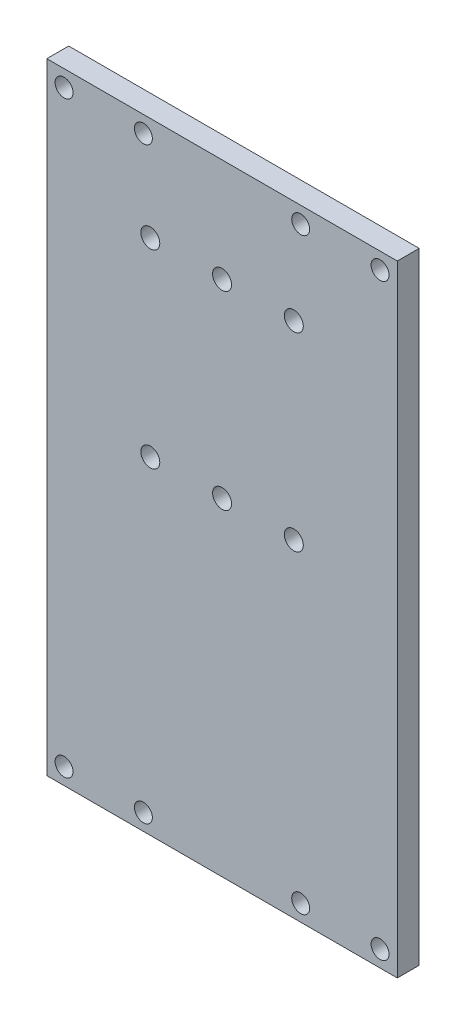
SolidWorks part; units mm, degrees
ref_plane "Plano frontal" through (0, 0, 0) normal (0, 0, 1) x (1, 0, 0)
ref_plane "Plano superior" through (0, 0, 0) normal (0, 1, 0) x (1, 0, 0)
ref_plane "Plano direito" through (0, 0, 0) normal (1, 0, 0) x (0, 0, -1)
sketch "Esboço1" plane through (0, 0, 0) normal (0, 0, 1) x (1, 0, 0)
  line L0 (50.8, 90) -> (-50.8, -90) construction
  line L1 (-50.8, 90) -> (50.8, 90)
  line L2 (-50.8, 90) -> (-50.8, -90)
  line L3 (-50.8, -90) -> (50.8, -90)
  line L4 (50.8, 90) -> (50.8, -90)
  dimension "D1" = 101.6
  dimension "D2" = 180
extrude "Ressalto-extrusão1" add sketch "Esboço1" along normal blind 6.35
sketch "Esboço2" plane through (0, 0, 6.35) normal (0, 0, 1) x (1, 0, 0)
  line L0 (-50.8, 0) -> (50.8, 0) construction
  line L1 (-50.8, 90) -> (-50.8, -90) construction
  line L2 (50.8, -90) -> (50.8, 90) construction
  line L3 (-50.8, 85.24) -> (50.8, 85.24) construction
  line L4 (50.8, 90) -> (-50.8, 90) construction
  line L5 (0, 90) -> (0, 0) construction
  circle A0 centre (-45.8, 85.24) radius 2.6
  circle A1 centre (-22.8, 85.24) radius 2.6
  circle A2 centre (22.8, 85.24) radius 2.6
  circle A3 centre (45.8, 85.24) radius 2.6
  circle A4 centre (45.8, -85.24) radius 2.6
  circle A5 centre (22.8, -85.24) radius 2.6
  circle A6 centre (-22.8, -85.24) radius 2.6
  circle A7 centre (-45.8, -85.24) radius 2.6
  dimension "D2" = 5.2
  dimension "D3" = 5.2
  dimension "D1" = 4.76
  dimension "D4" = 5
  dimension "D5" = 28
extrude "Corte-extrusão1" cut sketch "Esboço2" against normal up to next
sketch "Esboço3" plane through (0, 0, 6.35) normal (0, 0, 1) x (1, 0, 0)
  line L0 (-50.8, -90) -> (50.8, -90) construction
  line L1 (-20.8, 60) -> (20.8, 60) construction
  line L2 (-20.8, 60) -> (-20.8, 5) construction
  line L3 (-20.8, 5) -> (20.8, 5) construction
  line L4 (20.8, 60) -> (20.8, 5) construction
  line L5 (-50.8, 90) -> (-50.8, -90) construction
  line L6 (-20.8, 32.5) -> (20.8, 32.5) construction
  line L8 (0, 5) -> (0, 32.5) construction
  circle A0 centre (-20.8, 5) radius 2.75
  circle A1 centre (0, 5) radius 2.75
  circle A2 centre (20.8, 5) radius 2.75
  circle A3 centre (20.8, 60) radius 2.75
  circle A4 centre (0, 60) radius 2.75
  circle A5 centre (-20.8, 60) radius 2.75
  dimension "D5" = 5.5
  dimension "D6" = 5.5
  dimension "D1" = 95
  dimension "D2" = 150
  dimension "D3" = 30
  dimension "D4" = 71.6
extrude "Corte-extrusão2" cut sketch "Esboço3" against normal up to next
